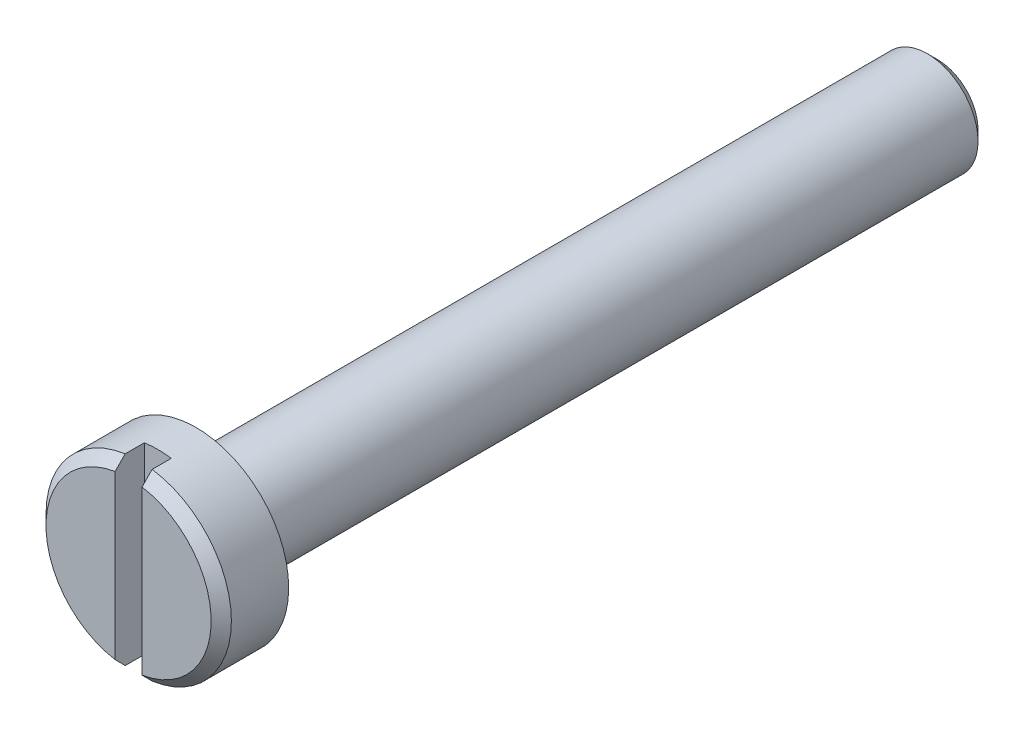
SolidWorks part; units mm, degrees
ref_plane "Front Plane" through (0, 0, 0) normal (0, 0, 1) x (1, 0, 0)
ref_plane "Top Plane" through (0, 0, 0) normal (0, 1, 0) x (1, 0, 0)
ref_plane "Right Plane" through (0, 0, 0) normal (1, 0, 0) x (0, 0, -1)
sketch "Sketch1" plane through (0, 0, 0) normal (0, 0, 1) x (1, 0, 0)
  circle A0 centre (0, 0) radius 1.5
extrude "Boss-Extrude1" add sketch "Sketch1" against normal blind 22
sketch "Sketch2" plane through (0, 0, 0) normal (0, 0, 1) x (1, 0, 0)
  circle A0 centre (0, 0) radius 2.75
extrude "Boss-Extrude2" add sketch "Sketch2" along normal blind 2
chamfer "Chamfer1" distance 0.3 angle 45 2 edges at (1.5, 0, -22) (2.75, 0, 2)
sketch "Sketch3" plane through (0, 0, 0) normal (0, 1, 0) x (1, 0, 0)
  line L5 (0.4, -2.8327) -> (0.4, -1.1327)
  line L6 (0.4, -2.8327) -> (-0.4, -2.8327)
  line L7 (0.4, -1.1327) -> (-0.4, -1.1327)
  line L8 (-0.4, -2.8327) -> (-0.4, -1.1327)
  line L9 (0.4, -2.8327) -> (-0.4, -1.1327) construction
  line L10 (0.4, -1.1327) -> (-0.4, -2.8327) construction
  line L11 (0, 0) -> (0, 0.9451) construction
  point P1 (0, -1.9827)
  dimension "D1" = 0.85
  dimension "D2" = 0.8
extrude "Cut-Extrude1" cut sketch "Sketch3" against normal through all both and the other way through all
